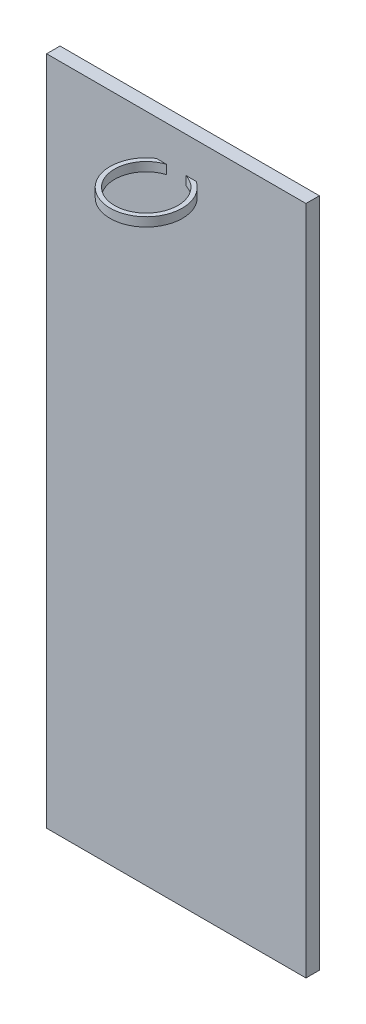
SolidWorks part; units mm, degrees
ref_plane "Top plane" through (0, 0, 0) normal (0, 0, 1) x (1, 0, 0)
ref_plane "Right plane" through (0, 0, 0) normal (0, 1, 0) x (1, 0, 0)
ref_plane "Front plane" through (0, 0, 0) normal (1, 0, 0) x (0, 0, -1)
sketch "Sketch1" plane through (0, 0, 0) normal (0, 0, 1) x (1, 0, 0)
  line L1 (52.9772, 89.7731) -> (110.9772, 89.7731)
  line L2 (52.9772, 89.7731) -> (52.9772, -60.2269)
  line L3 (52.9772, -60.2269) -> (110.9772, -60.2269)
  line L4 (110.9772, 89.7731) -> (110.9772, -60.2269)
extrude "Boss-Extrude1" add sketch "Sketch1" along normal blind 3
ref_plane "Plane1" through (0, 79.7731, 0) normal (0, 1, 0) x (1, 0, 0)
sketch "Sketch2" plane through (0, 79.7731, 0) normal (0, 1, 0) x (1, 0, 0)
  circle A0 centre (81.9772, -9.7245) radius 7.0762
extrude "Extrude-Thin1" add sketch "Sketch2" along normal blind 2 thin
